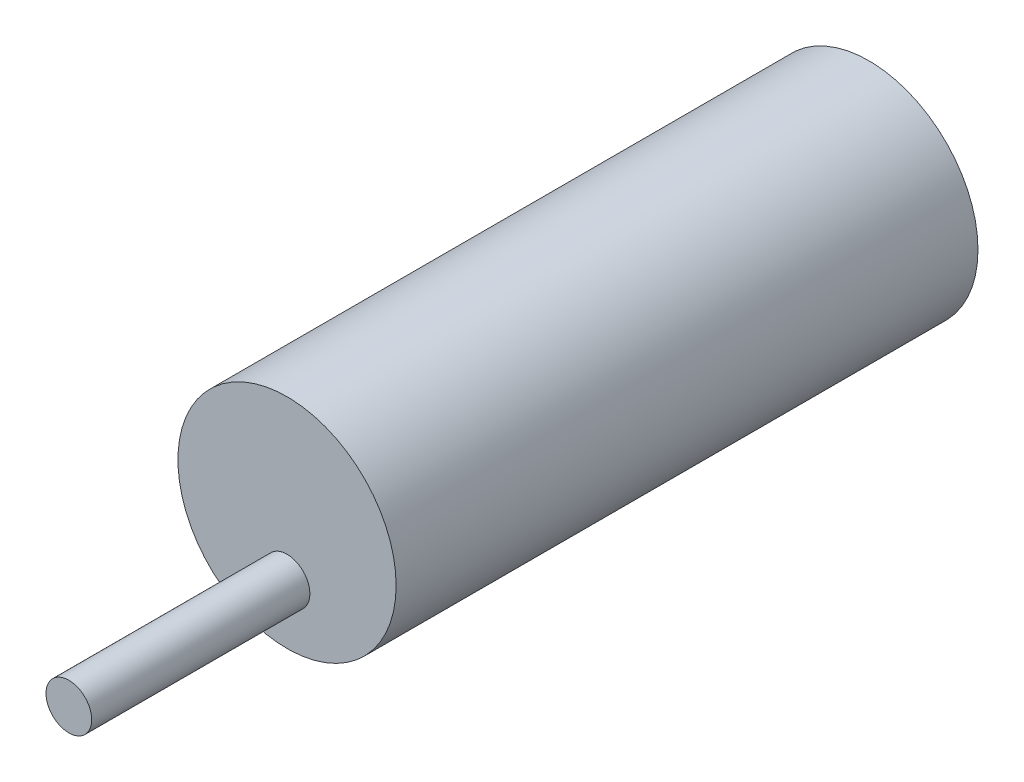
SolidWorks part; units mm, degrees
ref_plane "Front Plane" through (0, 0, 0) normal (0, 0, 1) x (1, 0, 0)
ref_plane "Top Plane" through (0, 0, 0) normal (0, 1, 0) x (1, 0, 0)
ref_plane "Right Plane" through (0, 0, 0) normal (1, 0, 0) x (0, 0, -1)
sketch "Sketch1" plane through (0, 0, 0) normal (0, 0, 1) x (1, 0, 0)
  circle A0 centre (0, 0) radius 19.05
  dimension "D1" = 38.1
extrude "Boss-Extrude1" add sketch "Sketch1" along normal blind 101.6
ref_plane "Plane1" through (0, 0, 101.6) normal (0, 0, 1) x (1, 0, 0)
sketch "Sketch2" plane through (0, 0, 101.6) normal (0, 0, 1) x (1, 0, 0)
  circle A0 centre (0, -8.7679) radius 3.9878
  dimension "D1" = 7.9756
  dimension "D2" = 8.7679
extrude "Boss-Extrude2" add sketch "Sketch2" along normal blind 38.1
